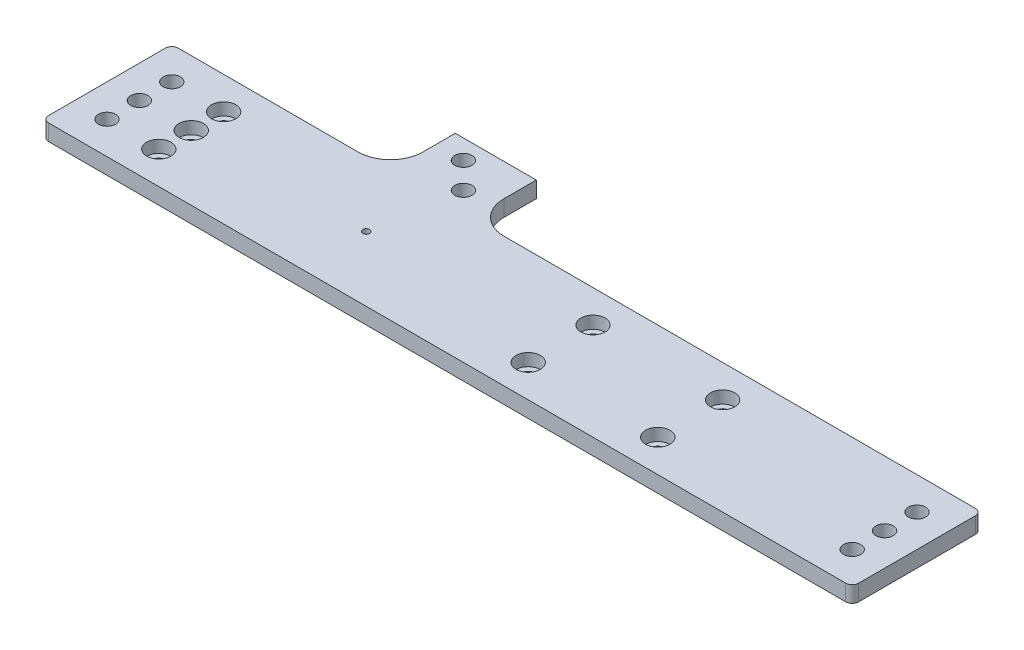
SolidWorks part; units mm, degrees
material "6061-T6 (SS)"
ref_plane "Front" through (0, 0, 0) normal (0, 0, 1) x (1, 0, 0)
ref_plane "Top" through (0, 0, 0) normal (0, 1, 0) x (1, 0, 0)
ref_plane "Right" through (0, 0, 0) normal (1, 0, 0) x (0, 0, -1)
sketch "Sketch1" plane through (0, 0, 0) normal (0, 1, 0) x (1, 0, 0)
  line L1 (-158.75, -25.4) -> (158.75, -25.4)
  line L2 (-158.75, -25.4) -> (-158.75, 25.4)
  line L3 (-158.75, 25.4) -> (158.75, 25.4)
  line L4 (158.75, -25.4) -> (158.75, 25.4)
  line L5 (-158.75, -25.4) -> (158.75, 25.4) construction
  line L6 (-158.75, 25.4) -> (158.75, -25.4) construction
  point P0 (0, 0)
  dimension "D1" = 50.8
  dimension "D2" = 317.5
extrude "Boss-Extrude1" add sketch "Sketch1" along normal blind 6.35
hole_wizard "CBORE for #10 Socket Head Cap Screw1" positions "Sketch2" profile "Sketch4" counterbore size "#10" standard "ANSI Inch" end condition through all
sketch "Sketch2" plane through (0, 6.35, 0) normal (0, 1, 0) x (1, 0, 0)
  line L2 (158.75, 25.4) -> (-158.75, 25.4) construction
  line L6 (-158.75, -25.4) -> (158.75, -25.4) construction
  line L8 (-158.75, 25.4) -> (-158.75, -25.4) construction
  line L12 (158.75, -25.4) -> (158.75, 25.4) construction
  line L15 (19.05, 12.7) -> (19.05, 25.4) construction
  line L17 (19.05, -12.7) -> (19.05, -25.4) construction
  line L18 (-125.73, -25.4) -> (-125.73, -12.7) construction
  line L20 (-125.73, 0) -> (-125.73, 12.7) construction
  line L21 (-125.73, 12.7) -> (-125.73, 25.4) construction
  line L22 (-125.73, 0) -> (-125.73, -12.7) construction
  point P64 (19.05, 12.7)
  point P66 (69.85, 12.7)
  point P68 (19.05, -12.7)
  point P70 (69.85, -12.7)
  point P92 (-125.73, 12.7)
  point P94 (-125.73, 0)
  point P102 (-125.73, -12.7)
  dimension "D2" = 50.8
  dimension "D3" = 25.4
  dimension "D4" = 88.9
  dimension "D5" = 33.02
sketch "Sketch4" plane through (-125.73, 6.35, 12.7) normal (1, 0, 0) x (0, 0, 1)
  line L0 (0, 0) -> (0, 6.35)
  line L1 (0, 6.35) -> (2.5527, 6.35)
  line L3 (2.5527, 6.35) -> (2.5527, 4.826)
  line L4 (2.5527, 4.826) -> (4.7625, 4.826)
  line L5 (4.7625, 4.826) -> (4.7625, 0)
  line L7 (4.7625, 0) -> (0, 0)
  line L11 (0, -6.35) -> (0, 107.95) construction
  dimension "Thru Hole Dia." = 5.1054
  dimension "Thru Hole Depth" = 6.35
  dimension "C'Bore Dia." = 9.525
  dimension "C'Bore Depth" = 4.826
sketch "Sketch7" plane through (0, 0, 0) normal (0, -1, 0) x (1, 0, 0)
  line L0 (-146.05, 25.4) -> (-146.05, 12.7) construction
  line L1 (-158.75, 25.4) -> (158.75, 25.4) construction
  line L2 (-146.05, 12.7) -> (-146.05, 0) construction
  line L3 (-146.05, 0) -> (-146.05, -12.7) construction
  line L4 (-146.05, -12.7) -> (-146.05, -25.4) construction
  line L5 (158.75, -25.4) -> (-158.75, -25.4) construction
  line L7 (-158.75, -25.4) -> (-158.75, 25.4) construction
  line L8 (146.05, 25.4) -> (146.05, 12.7) construction
  line L9 (146.05, 12.7) -> (146.05, 0) construction
  line L10 (146.05, 0) -> (146.05, -12.7) construction
  line L11 (146.05, -12.7) -> (146.05, -25.4) construction
  line L13 (158.75, 25.4) -> (158.75, -25.4) construction
  point P0 (-146.05, 12.7)
  point P2 (-146.05, 0)
  point P4 (-146.05, -12.7)
  point P6 (146.05, 12.7)
  point P8 (146.05, 0)
  point P10 (146.05, -12.7)
  dimension "D1" = 12.7
  dimension "D2" = 12.7
hole_wizard "1/4 Clearance Hole2" positions "Sketch7" profile "Sketch6" hole size "1/4" standard "ANSI Inch" end condition through all
sketch "Sketch6" plane through (-146.05, 0, 12.7) normal (1, 0, 0) x (0, 0, -1)
  line L0 (0, 0) -> (0, 6.35)
  line L1 (0, 6.35) -> (3.3782, 6.35)
  line L2 (3.3782, 6.35) -> (3.3782, 0)
  line L5 (3.3782, 0) -> (0, 0)
  line L11 (0, -6.35) -> (0, 107.95) construction
  dimension "Thru Hole Dia." = 6.7564
  dimension "Thru Hole Depth" = 6.35
sketch "Sketch10" plane through (0, 0, 0) normal (0, -1, 0) x (-1, 0, 0)
  line L0 (158.75, 25.4) -> (158.75, -25.4) construction
  point P0 (57.15, 0)
  dimension "D1" = 101.6
hole_wizard "#6-32 Tapped Hole1" positions "Sketch10" profile "Sketch9" tap size "#6-32" standard "ANSI Inch" end condition through all
sketch "Sketch9" plane through (-57.15, 0, 0) normal (1, 0, 0) x (0, 0, -1)
  line L0 (0, 0) -> (0, 6.35)
  line L1 (0, 6.35) -> (1.3525, 6.35)
  line L2 (1.3525, 6.35) -> (1.3525, 0)
  line L5 (1.3525, 0) -> (0, 0)
  line L11 (0, -6.35) -> (0, 107.95) construction
  dimension "Thru Tap Drill Dia." = 2.7051
  dimension "Thru Tap Drill Depth" = 6.35
cosmetic thread "Hole Thread1" parameters "D2"=3.5052
sketch "Sketch11" plane through (0, 0, 0) normal (0, -1, 0) x (1, 0, 0)
  line L0 (158.75, -25.4) -> (-158.75, -25.4) construction
  line L1 (-70.0118, -25.4) -> (-48.1024, -25.4)
  line L2 (-70.0118, -25.4) -> (-70.0118, -45.81)
  line L3 (-70.0118, -45.81) -> (-48.1024, -45.81)
  line L4 (-48.1024, -25.4) -> (-48.1024, -45.81)
extrude "Boss-Extrude2" [suppressed] add sketch "Sketch11" against normal up to surface (6.35 mm away)
sketch "Sketch12" plane through (0, 6.35, 0) normal (0, 1, 0) x (1, 0, 0)
  line L5 (-158.75, 25.4) -> (-158.75, -25.4) construction
  line L6 (-73.025, 25.4) -> (-73.025, 50.8)
  line L7 (158.75, 25.4) -> (-158.75, 25.4) construction
  line L8 (-73.025, 50.8) -> (-41.275, 50.8)
  line L9 (-41.275, 50.8) -> (-41.275, 25.4)
  line L10 (-73.025, 25.4) -> (-41.275, 25.4)
  dimension "D4" = 85.725
  dimension "D5" = 25.4
  dimension "D6" = 31.75
extrude "Boss-Extrude3" add sketch "Sketch12" against normal up to surface (6.35 mm away) up to face at (-57.15, 0, -1.3526)
sketch "Sketch15" plane through (0, 0, 0) normal (0, -1, 0) x (-1, 0, 0)
  point P0 (62.23, 43.18)
  point P3 (52.07, 33.02)
hole_wizard "1/4 Clearance Hole1" positions "Sketch15" profile "Sketch14" hole size "1/4" standard "ANSI Inch" end condition through all
sketch "Sketch14" plane through (-62.23, 0, -43.18) normal (1, 0, 0) x (0, 0, -1)
  line L0 (0, 0) -> (0, 6.35)
  line L1 (0, 6.35) -> (3.3782, 6.35)
  line L2 (3.3782, 6.35) -> (3.3782, 0)
  line L5 (3.3782, 0) -> (0, 0)
  line L11 (0, -6.35) -> (0, 107.95) construction
  dimension "Thru Hole Dia." = 6.7564
  dimension "Thru Hole Depth" = 6.35
fillet "Fillet1" radius 12.7 2 edges at (-41.275, 3.175, -25.4) (-73.025, 3.175, -25.4)
fillet "Fillet2" radius 2.54 4 edges at (158.75, 3.175, -25.4) (158.75, 3.175, 25.4) (-158.75, 3.175, 25.4) (-158.75, 3.175, -25.4)
